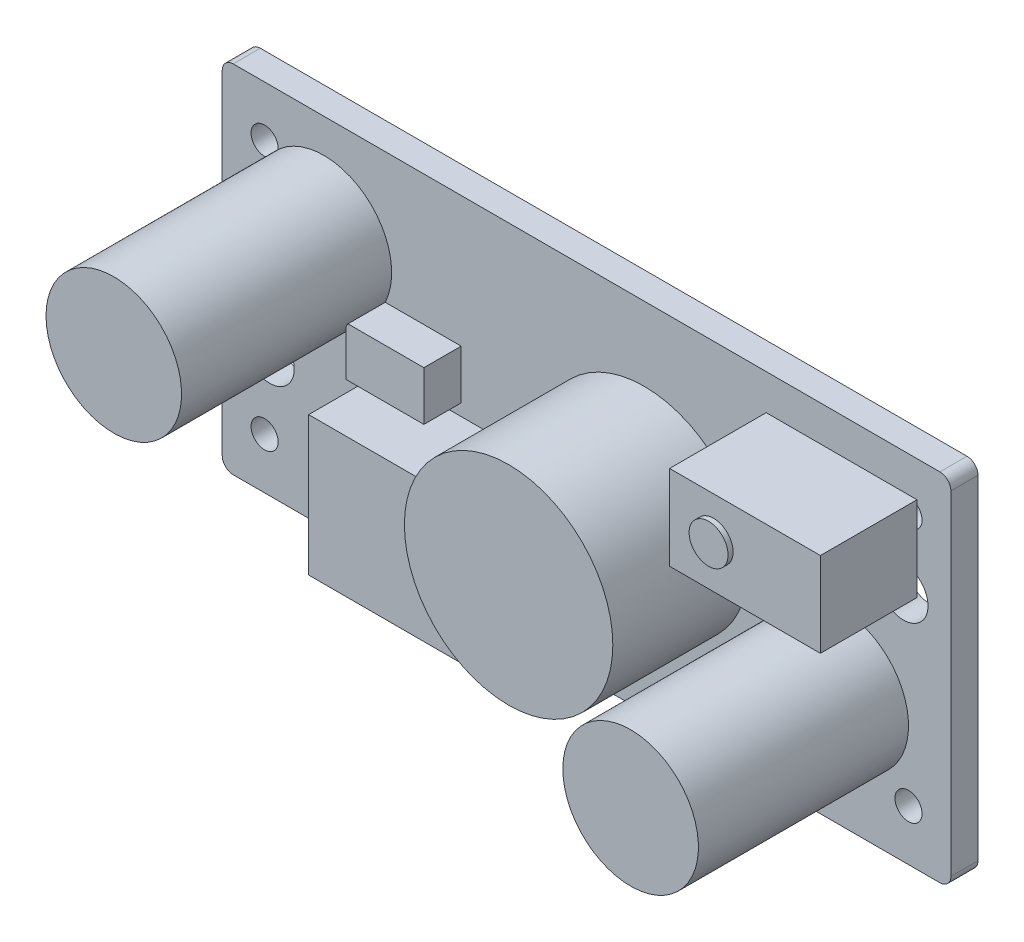
SolidWorks part; units mm, degrees
ref_plane "前视基准面" through (0, 0, 0) normal (0, 0, 1) x (1, 0, 0)
ref_plane "上视基准面" through (0, 0, 0) normal (0, 1, 0) x (1, 0, 0)
ref_plane "右视基准面" through (0, 0, 0) normal (1, 0, 0) x (0, 0, -1)
other "Configuration Table"
sketch "PCB_43x21x1p6_Sketch" plane through (0, 0, 0) normal (0, 0, 1) x (1, 0, 0)
  line L0 (-20.85, -10.5) -> (20.85, -10.5)
  line L1 (21.5, -9.85) -> (21.5, 9.85)
  line L2 (20.85, 10.5) -> (-20.85, 10.5)
  line L3 (-21.5, 9.85) -> (-21.5, -9.85)
  arc A0 (20.85, -10.5) -> (21.5, -9.85) centre (20.85, -9.85) ccw
  arc A1 (21.5, 9.85) -> (20.85, 10.5) centre (20.85, 9.85) ccw
  arc A2 (-20.85, 10.5) -> (-21.5, 9.85) centre (-20.85, 9.85) ccw
  arc A3 (-21.5, -9.85) -> (-20.85, -10.5) centre (-20.85, -9.85) ccw
  circle A4 centre (-19, -7.5) radius 0.8
  circle A5 centre (-19, 7.5) radius 0.8
  circle A6 centre (19, -7.5) radius 0.8
  circle A7 centre (19, 7.5) radius 0.8
  circle A8 centre (-18.7, -3.3) radius 1.45
  circle A9 centre (18.7, 3.3) radius 1.45
extrude "PCB_43x21x1p6" add sketch "PCB_43x21x1p6_Sketch" along normal blind 1.6 separate body
sketch "LM2596S_TO263_Sketch" plane through (0, 0, 0) normal (0, 0, 1) x (1, 0, 0)
  line L0 (-12, -9) -> (-3, -9)
  line L1 (-3, -9) -> (-3, -0.8)
  line L2 (-3, -0.8) -> (-12, -0.8)
  line L3 (-12, -0.8) -> (-12, -9)
extrude "LM2596S_TO263" add sketch "LM2596S_TO263_Sketch" along normal blind 4.4 from offset 1.6 separate body
sketch "Trim_pot_Sketch" plane through (0, 0, 0) normal (0, 0, 1) x (1, 0, 0)
  line L0 (10.6, 3.4) -> (19.5, 3.4)
  line L1 (19.5, 3.4) -> (19.5, 8.4)
  line L2 (19.5, 8.4) -> (10.6, 8.4)
  line L3 (10.6, 8.4) -> (10.6, 3.4)
extrude "Trim_pot" add sketch "Trim_pot_Sketch" along normal blind 5.7 from offset 1.6 separate body
sketch "Trim_Adjust_Sketch" plane through (0, 0, 0) normal (0, 0, 1) x (1, 0, 0)
  circle A0 centre (13.2, 6) radius 1.15
extrude "Trim_Adjust" add sketch "Trim_Adjust_Sketch" along normal blind 0.3 from offset 7.3 separate body
sketch "Shielded_inductor_Sketch" plane through (0, 0, 0) normal (0, 0, 1) x (1, 0, 0)
  circle A0 centre (3.4, 0) radius 6.15
extrude "Shielded_inductor" add sketch "Shielded_inductor_Sketch" along normal blind 8 from offset 1.6 separate body
sketch "Input_capacitor_Sketch" plane through (0, 0, 0) normal (0, 0, 1) x (1, 0, 0)
  circle A0 centre (-15.5, 4.5) radius 4
extrude "Input_capacitor" add sketch "Input_capacitor_Sketch" along normal blind 12.4 from offset 1.6 separate body
sketch "Output_capacitor_Sketch" plane through (0, 0, 0) normal (0, 0, 1) x (1, 0, 0)
  circle A0 centre (15, -3.4) radius 4
extrude "Output_capacitor" add sketch "Output_capacitor_Sketch" along normal blind 12.4 from offset 1.6 separate body
sketch "Schottky_diode_Sketch" plane through (0, 0, 0) normal (0, 0, 1) x (1, 0, 0)
  line L0 (-12, -0.1) -> (-7.4, -0.1)
  line L1 (-7.4, -0.1) -> (-7.4, 2.8)
  line L2 (-7.4, 2.8) -> (-12, 2.8)
  line L3 (-12, 2.8) -> (-12, -0.1)
extrude "Schottky_diode" add sketch "Schottky_diode_Sketch" along normal blind 2.2 from offset 1.6 separate body
